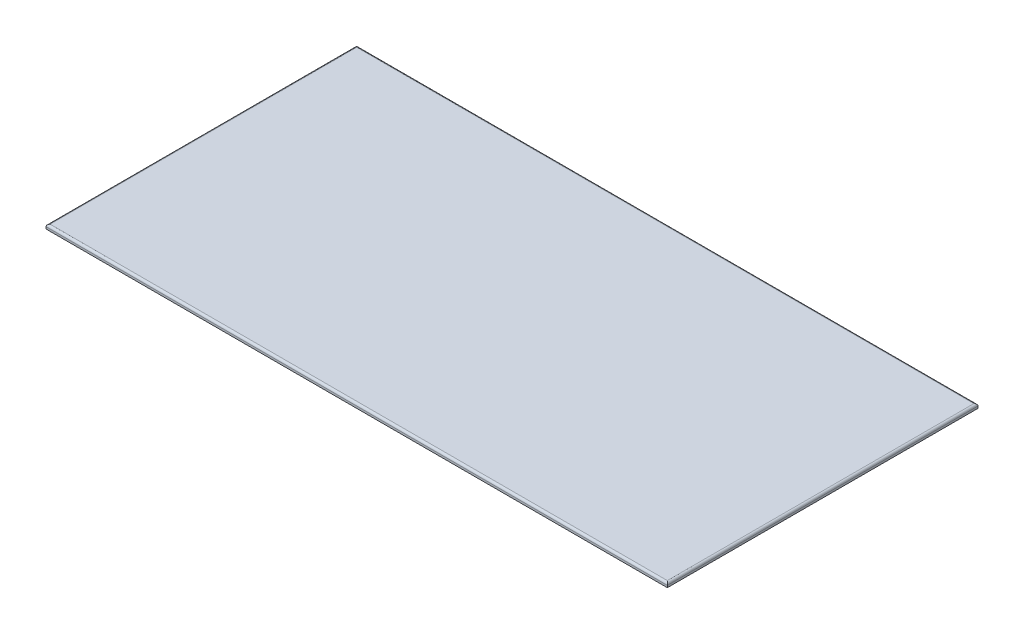
SolidWorks part; units mm, degrees
material "Керамика фарфор"
ref_plane "Спереди" through (0, 0, 0) normal (0, 0, 1) x (1, 0, 0)
ref_plane "Сверху" through (0, 0, 0) normal (0, 1, 0) x (1, 0, 0)
ref_plane "Справа" through (0, 0, 0) normal (1, 0, 0) x (0, 0, -1)
other "Configuration Table"
sketch "Эскиз1" plane through (0, 0, 0) normal (0, 1, 0) x (1, 0, 0)
  line L0 (0, 0) -> (1200, 600) construction
  line L1 (0, 0) -> (1200, 0)
  line L2 (0, 0) -> (0, 600)
  line L3 (0, 600) -> (1200, 600)
  line L4 (1200, 0) -> (1200, 600)
  point P5 (600, 300)
  dimension "D1" = 1200
  dimension "D2" = 600
extrude "Бобышка-Вытянуть1" add sketch "Эскиз1" along normal blind 8
fillet "Скругление1" radius 4 4 edges at (600, 8, -600) (1200, 8, -300) (600, 8, 0) (0, 8, -300)
